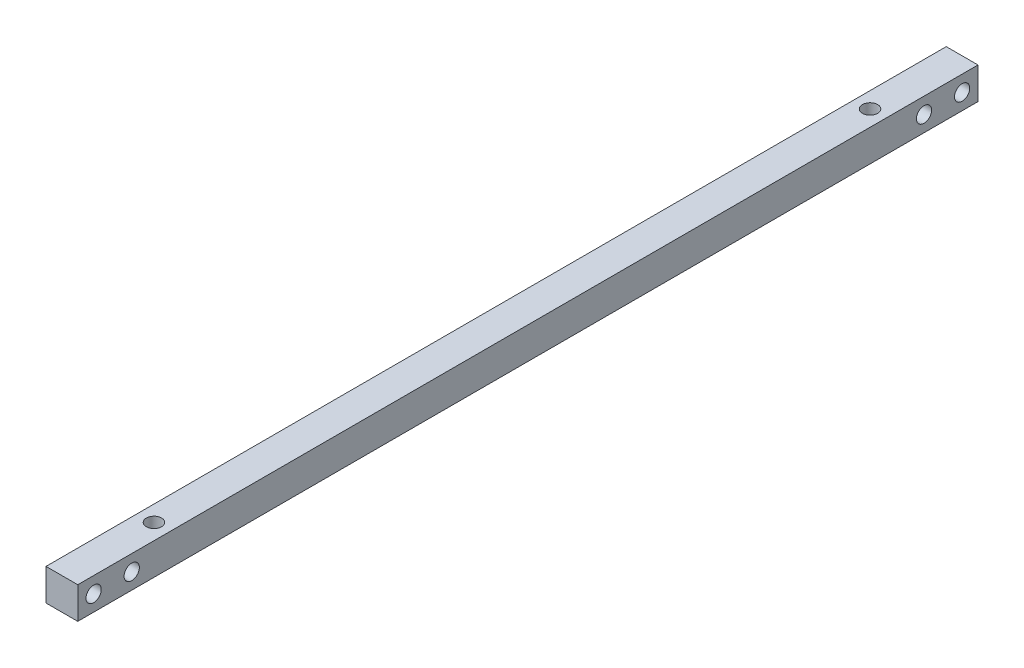
SolidWorks part; units mm, degrees
ref_plane "Alzado" through (0, 0, 0) normal (0, 0, 1) x (1, 0, 0)
ref_plane "Planta" through (0, 0, 0) normal (0, 1, 0) x (1, 0, 0)
ref_plane "Vista lateral" through (0, 0, 0) normal (1, 0, 0) x (0, 0, -1)
sketch "Croquis1" plane through (0, 0, 0) normal (1, 0, 0) x (0, 0, -1)
  line L0 (3.4375, 0) -> (-3.4375, 0) construction
  line L1 (-88.6, -3.125) -> (88.6, -3.125)
  line L2 (-88.6, -3.125) -> (-88.6, 3.125)
  line L3 (-88.6, 3.125) -> (88.6, 3.125)
  line L4 (88.6, -3.125) -> (88.6, 3.125)
  line L5 (0, 3.4375) -> (0, -3.4375) construction
  point P4 (0, -3.125)
  point P5 (-88.6, 0)
  dimension "D1" = 6.25
  dimension "D2" = 177.2
extrude "Saliente-Extruir1" add sketch "Croquis1" along normal mid plane 6.25
sketch "Croquis4" plane through (3.125, 0, 0) normal (1, 0, 0) x (0, 0, -1)
  line L0 (-88.6, 3.125) -> (-88.6, -3.125) construction
  line L1 (88.6, -3.125) -> (88.6, 3.125) construction
  line L2 (88.6, 0) -> (-88.6, 0) construction
  circle A0 centre (85.475, 0) radius 1.5
  circle A1 centre (77.975, 0) radius 1.5
  circle A2 centre (-85.475, 0) radius 1.5
  circle A3 centre (-77.975, 0) radius 1.5
  point P0 (-88.6, 0)
  point P1 (88.6, 0)
  point P8 (-85.475, 0)
  point P9 (-77.975, 0)
  point P10 (85.475, 0)
  point P11 (77.975, 0)
  dimension "D1" = 3.125
  dimension "D2" = 7.5
  dimension "D3" = 7.5
  dimension "D4" = 3.125
extrude "Cortar-Extruir1" cut sketch "Croquis4" against normal mid plane 30
sketch "Croquis5" plane through (0, -3.125, 0) normal (0, -1, 0) x (1, 0, 0)
  line L0 (3.125, 88.6) -> (-3.125, 88.6) construction
  line L1 (3.125, -88.6) -> (-3.125, -88.6) construction
  line L2 (0, -88.6) -> (0, 88.6) construction
  circle A0 centre (0, -70.475) radius 1.5
  circle A1 centre (0, 70.475) radius 1.5
  point P0 (0, 88.6)
  point P1 (0, -88.6)
  point P8 (0, 70.475)
  point P9 (0, -70.475)
  dimension "D1" = 18.125
  dimension "D2" = 18.125
extrude "Cortar-Extruir3" cut sketch "Croquis5" against normal blind 368
